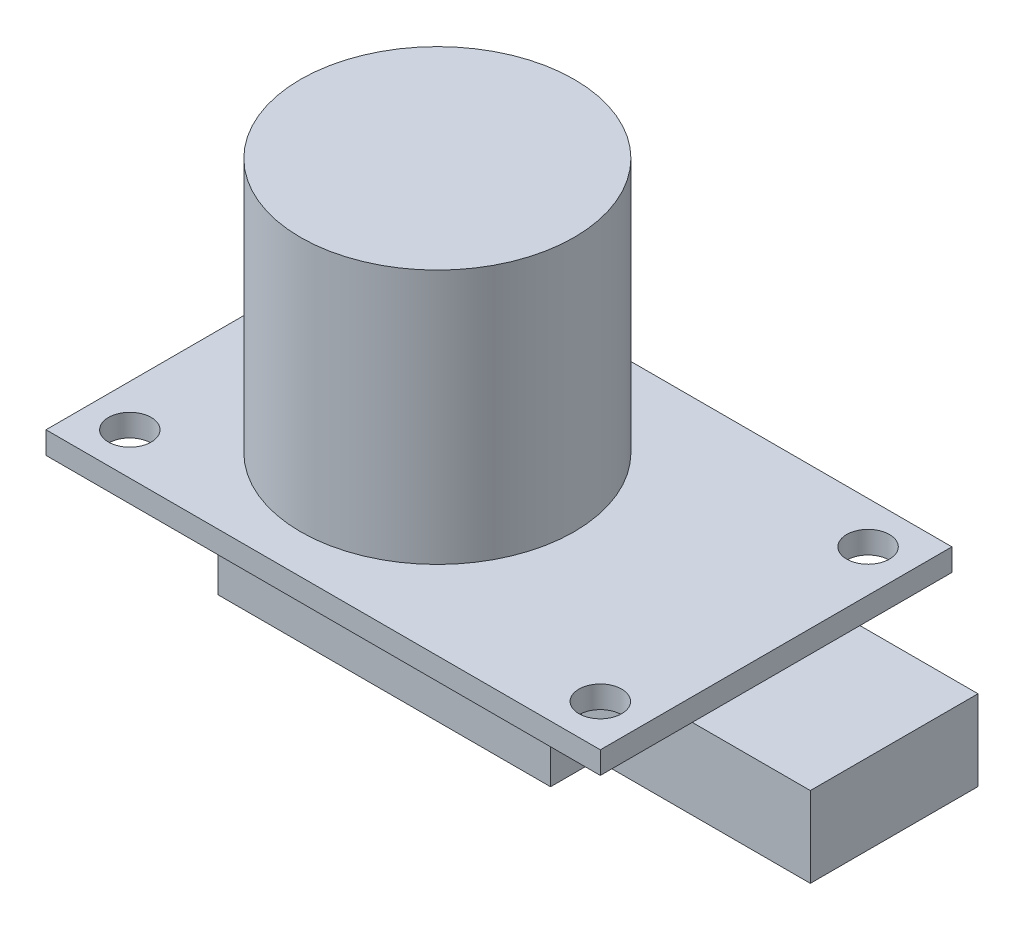
SolidWorks part; units mm, degrees
ref_plane "Front Plane" through (0, 0, 0) normal (0, 0, 1) x (1, 0, 0)
ref_plane "Top Plane" through (0, 0, 0) normal (0, 1, 0) x (1, 0, 0)
ref_plane "Right Plane" through (0, 0, 0) normal (1, 0, 0) x (0, 0, -1)
sketch "Sketch1" plane through (0, 0, 0) normal (0, 1, 0) x (1, 0, 0)
  line L0 (0, 0) -> (6.9678, 0) construction
  line L1 (-16.2, 10.275) -> (16.2, 10.275)
  line L2 (-16.2, 10.275) -> (-16.2, -10.275)
  line L3 (-16.2, -10.275) -> (16.2, -10.275)
  line L4 (16.2, 10.275) -> (16.2, -10.275)
  line L5 (-16.2, 10.275) -> (16.2, -10.275) construction
  line L6 (-16.2, -10.275) -> (16.2, 10.275) construction
  line L7 (0, 0) -> (0, 5.8489) construction
  circle A0 centre (-13.75, 7.825) radius 1.25
  circle A1 centre (-13.75, -7.825) radius 1.25
  circle A2 centre (13.75, -7.825) radius 1.25
  circle A3 centre (13.75, 7.825) radius 1.25
  point P0 (0, 0)
  dimension "D3" = 2.5
  dimension "D7" = 1.2
  dimension "D1" = 20.55
  dimension "D2" = 32.4
  dimension "D4" = 1.2
  dimension "D5" = 1.2
  dimension "D6" = 1.2
  dimension "D8" = 1.2
extrude "Boss-Extrude1" add sketch "Sketch1" along normal blind 1.3
sketch "Sketch2" plane through (0, 1.3, 0) normal (0, 1, 0) x (1, 0, 0)
  line L0 (-16.2, 10.275) -> (-16.2, -10.275) construction
  circle A0 centre (-3.6, 0) radius 8
  dimension "D1" = 16
  dimension "D2" = 4.6
extrude "Boss-Extrude2" add sketch "Sketch2" along normal blind 14.9
sketch "Sketch3" plane through (0, 0, 0) normal (0, -1, 0) x (1, 0, 0)
  line L1 (-9.7185, 6.7024) -> (9.7185, 6.7024)
  line L2 (-9.7185, 6.7024) -> (-9.7185, -6.7024)
  line L3 (-9.7185, -6.7024) -> (9.7185, -6.7024)
  line L4 (9.7185, 6.7024) -> (9.7185, -6.7024)
  line L5 (-9.7185, 6.7024) -> (9.7185, -6.7024) construction
  line L6 (-9.7185, -6.7024) -> (9.7185, 6.7024) construction
  point P0 (0, 0)
extrude "Boss-Extrude3" add sketch "Sketch3" along normal blind 5.6
sketch "Sketch4" plane through (0, 0, 0) normal (0, -1, 0) x (1, 0, 0)
  line L0 (16.2, 10.275) -> (16.2, -10.275) construction
  line L1 (9.3, 4.9) -> (23.1, 4.9)
  line L2 (9.3, 4.9) -> (9.3, -4.9)
  line L3 (9.3, -4.9) -> (23.1, -4.9)
  line L4 (23.1, 4.9) -> (23.1, -4.9)
  line L5 (9.3, 4.9) -> (23.1, -4.9) construction
  line L6 (9.3, -4.9) -> (23.1, 4.9) construction
  point P0 (16.2, 0)
  dimension "D1" = 6.9
  dimension "D2" = 9.8
extrude "Boss-Extrude4" add sketch "Sketch4" along normal blind 4.7
